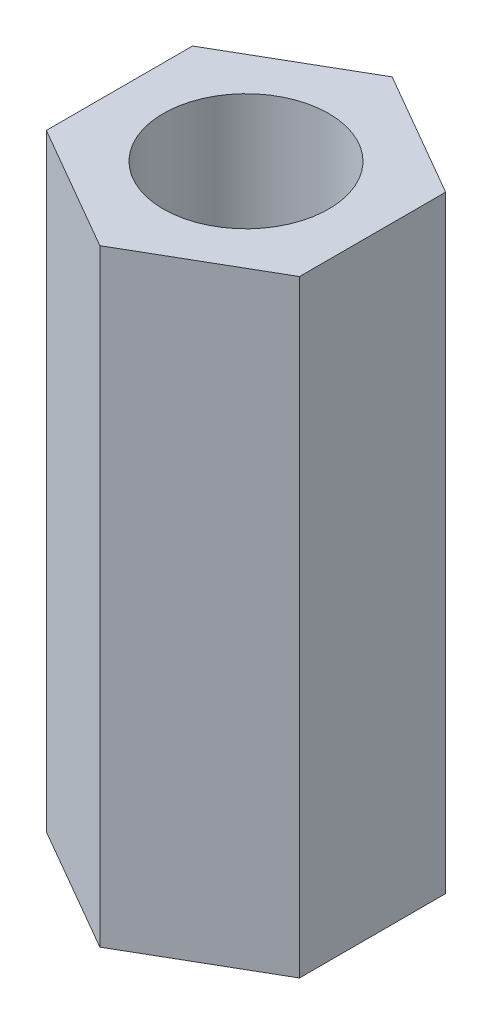
SolidWorks part; units mm, degrees
ref_plane "Front Plane" through (0, 0, 0) normal (0, 0, 1) x (1, 0, 0)
ref_plane "Top Plane" through (0, 0, 0) normal (0, 1, 0) x (1, 0, 0)
ref_plane "Right Plane" through (0, 0, 0) normal (1, 0, 0) x (0, 0, -1)
sketch "Sketch1" plane through (0, 0, 0) normal (0, 1, 0) x (1, 0, 0)
  line L0 (2.5002, 1.4435) -> (2.5002, -1.4435)
  line L1 (2.5002, -1.4435) -> (0, -2.887)
  line L2 (0, -2.887) -> (-2.5002, -1.4435)
  line L3 (-2.5002, -1.4435) -> (-2.5002, 1.4435)
  line L4 (-2.5002, 1.4435) -> (0, 2.887)
  line L5 (0, 2.887) -> (2.5002, 1.4435)
  circle A0 centre (0, 0) radius 1.635
  dimension "D1" = 3.27
  dimension "D3" = 2.887
  dimension "D4" = 2.887
  dimension "D5" = 2.887
  dimension "D6" = 2.887
  dimension "D7" = 2.887
extrude "Boss-Extrude1" add sketch "Sketch1" along normal blind 12
